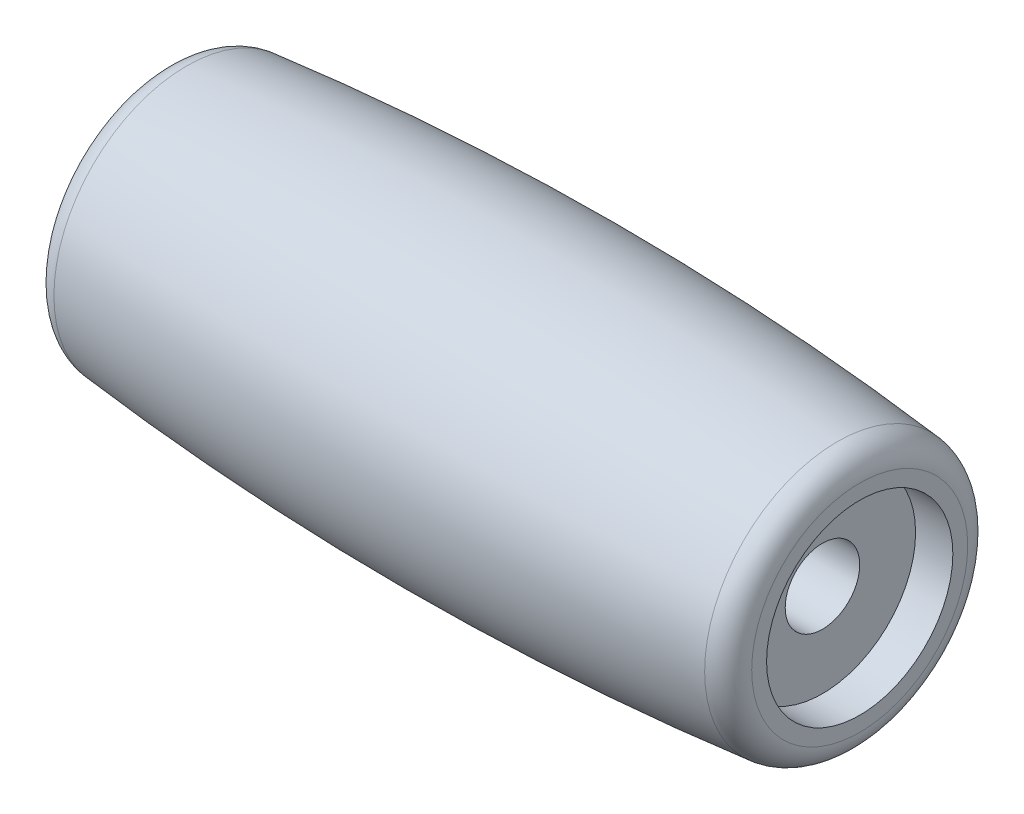
SolidWorks part; units mm, degrees
ref_plane "Front Plane" through (0, 0, 0) normal (0, 0, 1) x (1, 0, 0)
ref_plane "Top Plane" through (0, 0, 0) normal (0, 1, 0) x (1, 0, 0)
ref_plane "Right Plane" through (0, 0, 0) normal (1, 0, 0) x (0, 0, -1)
sketch "Sketch1" plane through (0, 0, 0) normal (0, 0, 1) x (1, 0, 0)
  line L0 (0, 6) -> (0, 0) construction
  line L1 (0, 0) -> (15.281, 0) construction
  line L2 (-12.5, 1.5) -> (12.5, 1.5)
  line L3 (12.5, 1.5) -> (12.5, 3.75)
  line L4 (12.5, 3.75) -> (14, 3.75)
  line L5 (14, 3.75) -> (14, 4.3486)
  line L6 (-14, 3.75) -> (-14, 4.3486)
  line L7 (-12.5, 3.75) -> (-14, 3.75)
  line L8 (-12.5, 1.5) -> (-12.5, 3.75)
  arc A0 (-13.1, 5.3436) -> (13.1, 5.3436) centre (0, -125.0417) cw
  arc A1 (14, 4.3486) -> (13.1, 5.3436) centre (13, 4.3486) ccw
  arc A2 (-14, 4.3486) -> (-13.1, 5.3436) centre (-13, 4.3486) cw
  point P13 (0, 1.5)
  point P16 (14, 5.25)
  point P19 (-14, 5.25)
  dimension "D7" = 1
  dimension "D1" = 1.5
  dimension "D2" = 3.75
  dimension "D3" = 1.5
  dimension "D4" = 1.5
  dimension "D5" = 14
  dimension "D6" = 6
revolve "Revolve1" add sketch "Sketch1" angle 360 about L1
